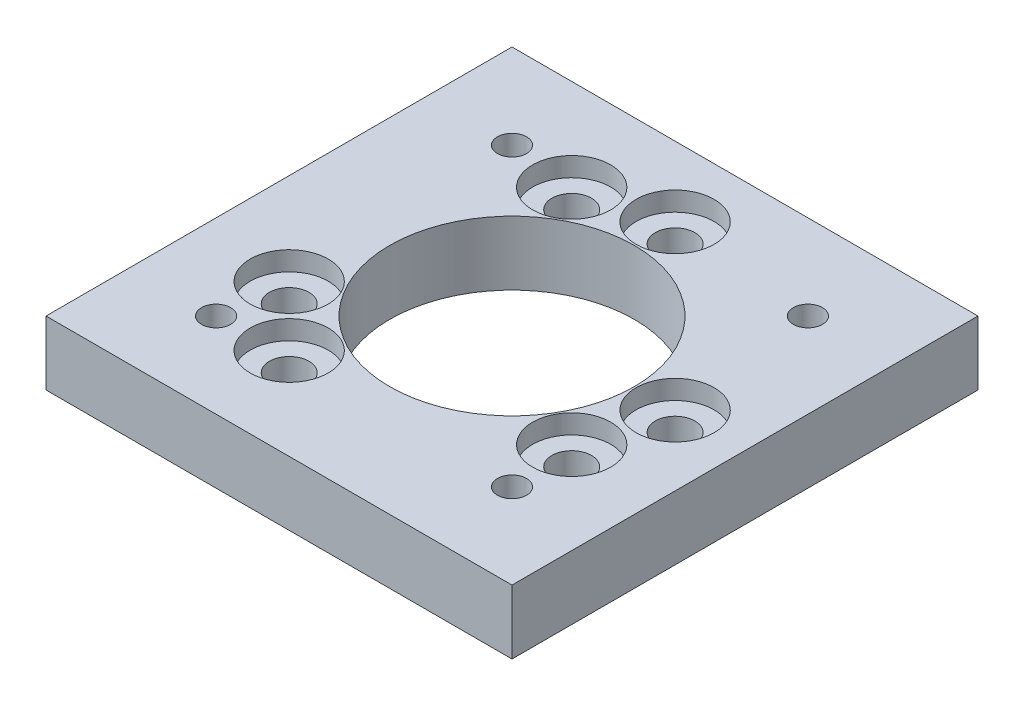
SolidWorks part; units mm, degrees
ref_plane "Front Plane" through (0, 0, 0) normal (0, 0, 1) x (1, 0, 0)
ref_plane "Top Plane" through (0, 0, 0) normal (0, 1, 0) x (1, 0, 0)
ref_plane "Right Plane" through (0, 0, 0) normal (1, 0, 0) x (0, 0, -1)
sketch "Sketch1" plane through (0, 0, 0) normal (0, 1, 0) x (1, 0, 0)
  line L1 (-20, -20) -> (20, -20)
  line L2 (-20, -20) -> (-20, 20)
  line L3 (-20, 20) -> (20, 20)
  line L4 (20, -20) -> (20, 20)
  line L5 (-20, -20) -> (20, 20) construction
  line L6 (-20, 20) -> (20, -20) construction
  point P0 (0, 0)
  dimension "D1" = 40
  dimension "D2" = 40
extrude "Boss-Extrude1" add sketch "Sketch1" along normal blind 5.5
sketch "Sketch2" plane through (0, 5.5, 0) normal (0, 1, 0) x (1, 0, 0)
  circle A0 centre (0, 0) radius 10.5
  dimension "D1" = 21
extrude "Cut-Extrude1" cut sketch "Sketch2" against normal up to next
sketch "Sketch3" plane through (0, 5.5, 0) normal (0, 1, 0) x (1, 0, 0)
  line L1 (12.7, -12.7) -> (-12.7, -12.7)
  line L2 (12.7, -12.7) -> (12.7, 12.7)
  line L3 (12.7, 12.7) -> (-12.7, 12.7)
  line L4 (-12.7, -12.7) -> (-12.7, 12.7)
  line L5 (12.7, -12.7) -> (-12.7, 12.7) construction
  line L6 (12.7, 12.7) -> (-12.7, -12.7) construction
  point P0 (0, 0)
  point P6 (0, 0)
  dimension "D1" = 25.4
  dimension "D2" = 25.4
hole_wizard "M3x0.5 Tapped Hole1" positions "Sketch4" profile "Sketch6" tap size "M3x0.5" standard "ANSI Metric"
sketch "Sketch4" plane through (0, 5.5, 0) normal (0, 1, 0) x (1, 0, 0)
  point P0 (-12.7, -12.7)
  point P3 (-12.7, 12.7)
  point P6 (12.7, 12.7)
  point P9 (12.7, -12.7)
sketch "Sketch6" plane through (-12.7, 5.5, 12.7) normal (1, 0, 0) x (0, 0, 1)
  line L0 (0, 0) -> (0, 15.9911)
  line L1 (0, 15.9911) -> (1.25, 15.24)
  line L2 (1.25, 15.24) -> (1.25, 0)
  line L5 (1.25, 0) -> (0, 0)
  line L10 (0, 15.9911) -> (-1.25, 15.24) construction
  line L11 (0, -6.35) -> (0, 107.95) construction
  dimension "Tap Drill Dia." = 2.5
  dimension "Tap Drill Depth" = 15.24
  dimension "Drill Angle" = 118
cosmetic thread "Hole Thread1" parameters "D1"=5.5, "D2"=3
cosmetic thread "Hole Thread2" parameters "D1"=5.5, "D2"=3
cosmetic thread "Hole Thread3" parameters "D1"=5.5, "D2"=3
cosmetic thread "Hole Thread4" parameters "D1"=5.5, "D2"=3
sketch "Sketch7" plane through (0, 5.5, 0) normal (0, 1, 0) x (1, 0, 0)
  line L0 (0, 0) -> (-12.7, -12.7) construction
  line L1 (-12.1244, -7) -> (0, 0) construction
  line L2 (0, 0) -> (-7, -12.1244) construction
  circle A0 centre (0, 0) radius 14
  point P3 (-12.1244, -7)
  point P6 (-7, -12.1244)
  dimension "D1" = 28
  dimension "D2" = 15
  dimension "D3" = 15
hole_wizard "CBORE for M3 SBHCS1" positions "Sketch8" profile "Sketch10" counterbore size "M3" standard "ANSI Metric"
sketch "Sketch8" plane through (0, 5.5, 0) normal (0, 1, 0) x (1, 0, 0)
  point P0 (-12.1244, -7)
  point P3 (-7, -12.1244)
sketch "Sketch10" plane through (-12.1244, 5.5, 7) normal (1, 0, 0) x (0, 0, 1)
  line L0 (0, 0) -> (0, 16.2615)
  line L1 (0, 16.2615) -> (1.7, 15.24)
  line L2 (1.7, 15.24) -> (1.7, 1.65)
  line L3 (1.7, 1.65) -> (3.35, 1.65)
  line L4 (3.35, 1.65) -> (3.35, 0)
  line L5 (3.35, 0) -> (0, 0)
  line L10 (0, 16.2615) -> (-1.7, 15.24) construction
  line L11 (0, -6.35) -> (0, 107.95) construction
  dimension "Hole Dia." = 3.4
  dimension "Hole Depth" = 15.24
  dimension "C'Bore Dia." = 6.7
  dimension "C'Bore Depth" = 1.65
  dimension "Drill Angle" = 118
pattern_circular "CirPattern1" count 3 over 360 about axis through (0, 0, 0) along (0, 1, 0) of "CBORE for M3 SBHCS1"
